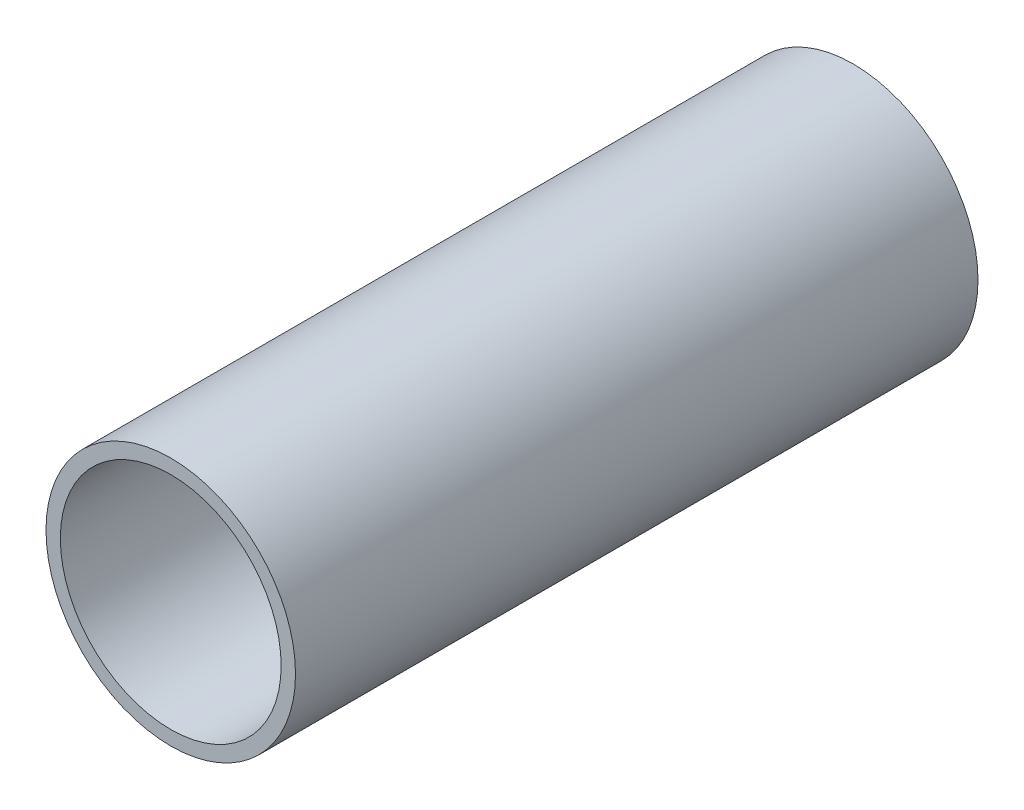
SolidWorks part; units mm, degrees
ref_plane "Front Plane" through (0, 0, 0) normal (0, 0, 1) x (1, 0, 0)
ref_plane "Top Plane" through (0, 0, 0) normal (0, 1, 0) x (1, 0, 0)
ref_plane "Right Plane" through (0, 0, 0) normal (1, 0, 0) x (0, 0, -1)
sketch "Sketch5" plane through (0, 0, 0) normal (0, 0, 1) x (1, 0, 0)
  circle A0 centre (0, 0) radius 87
  circle A1 centre (0, 0) radius 77
extrude "Boss-Extrude3" add sketch "Sketch5" along normal blind 476
sketch "Sketch7" plane through (0, 0, 0) normal (0, 1, 0) x (1, 0, 0)
  line L0 (-87, 0) -> (-87, -476) construction
  line L2 (-87, 0) -> (87, 0)
  spline S0 degree 2 poles (-87, 0) (0, 417.5584) (87, 0) knots 0 0 0 1 1 1
